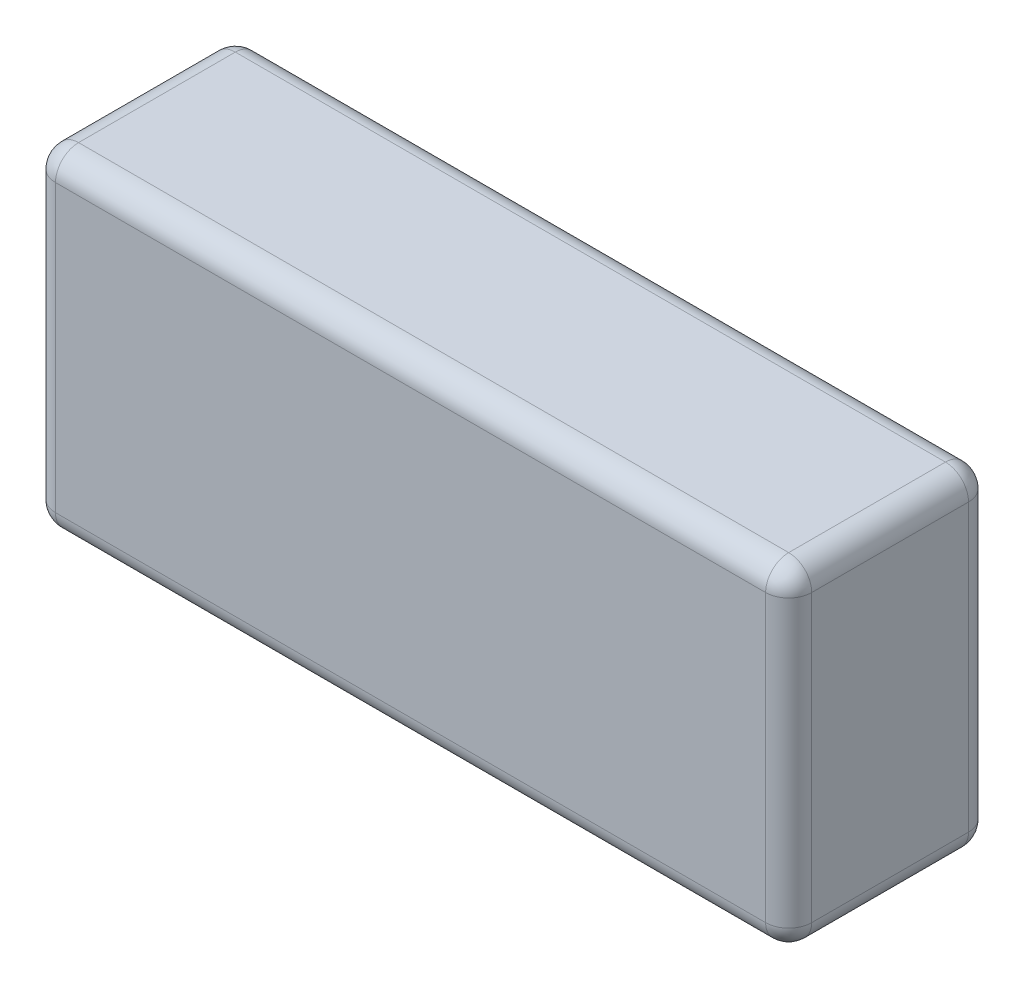
SolidWorks part; units mm, degrees
ref_plane "Front Plane" through (0, 0, 0) normal (0, 0, 1) x (1, 0, 0)
ref_plane "Top Plane" through (0, 0, 0) normal (0, 1, 0) x (1, 0, 0)
ref_plane "Right Plane" through (0, 0, 0) normal (1, 0, 0) x (0, 0, -1)
sketch "Sketch2" plane through (0, 0, 0) normal (0, 0, 1) x (1, 0, 0)
  line L1 (0, 0) -> (82, 0)
  line L2 (0, 0) -> (0, 36)
  line L3 (0, 36) -> (82, 36)
  line L4 (82, 0) -> (82, 36)
  dimension "D1" = 82
  dimension "D2" = 36
extrude "Boss-Extrude1" add sketch "Sketch2" along normal blind 22
fillet "Fillet1" radius 2.5 4 edges at (41, 0, 0) (41, 0, 22) (41, 36, 0) (41, 36, 22)
fillet "Fillet2" radius 2.5 16 edges at (0, 0.7322, 21.2678) (0, 18, 22) (0, 35.2678, 21.2678) (0, 36, 11) (0, 35.2678, 0.7322) (0, 18, 0) (0, 0.7322, 0.7322) (82, 0.7322, 21.2678) (82, 18, 22) (82, 35.2678, 21.2678) (82, 36, 11) (82, 35.2678, 0.7322) (82, 18, 0) (82, 0.7322, 0.7322) (82, 0, 11) (0, 0, 11)
